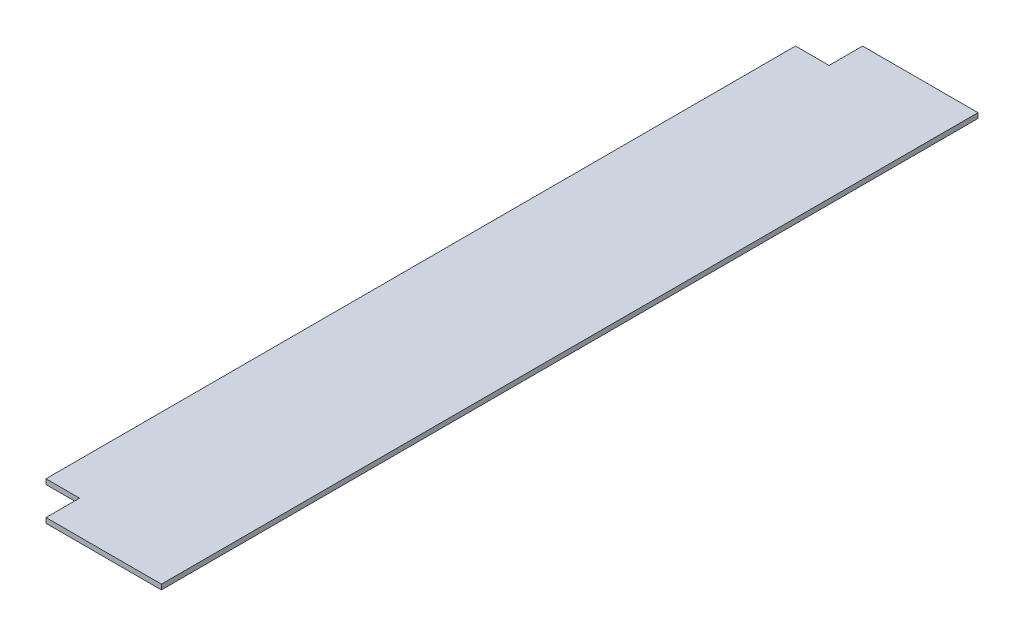
SolidWorks part; units mm, degrees
ref_plane "Front Plane" through (0, 0, 0) normal (0, 0, 1) x (1, 0, 0)
ref_plane "Top Plane" through (0, 0, 0) normal (0, 1, 0) x (1, 0, 0)
ref_plane "Right Plane" through (0, 0, 0) normal (1, 0, 0) x (0, 0, -1)
sketch "Sketch1" plane through (0, 0, 0) normal (0, 1, 0) x (1, 0, 0)
  line L13 (-66.9625, 365) -> (36.1975, 365)
  line L14 (-96.9625, 335) -> (-96.9625, -335)
  line L15 (-66.9625, -365) -> (36.1975, -365)
  line L16 (36.1975, 365) -> (36.1975, -365)
  line L19 (-96.9625, 335) -> (-66.9625, 335)
  line L20 (-66.9625, 365) -> (-66.9625, 335)
  line L23 (-96.9625, -335) -> (-66.9625, -335)
  line L24 (-66.9625, -365) -> (-66.9625, -335)
  dimension "D1" = 103.16
  dimension "D3" = 365
  dimension "D4" = 30
  dimension "D5" = 30
  dimension "D6" = 30
  dimension "D7" = 30
extrude "Boss-Extrude1" add sketch "Sketch1" along normal blind 4.5
